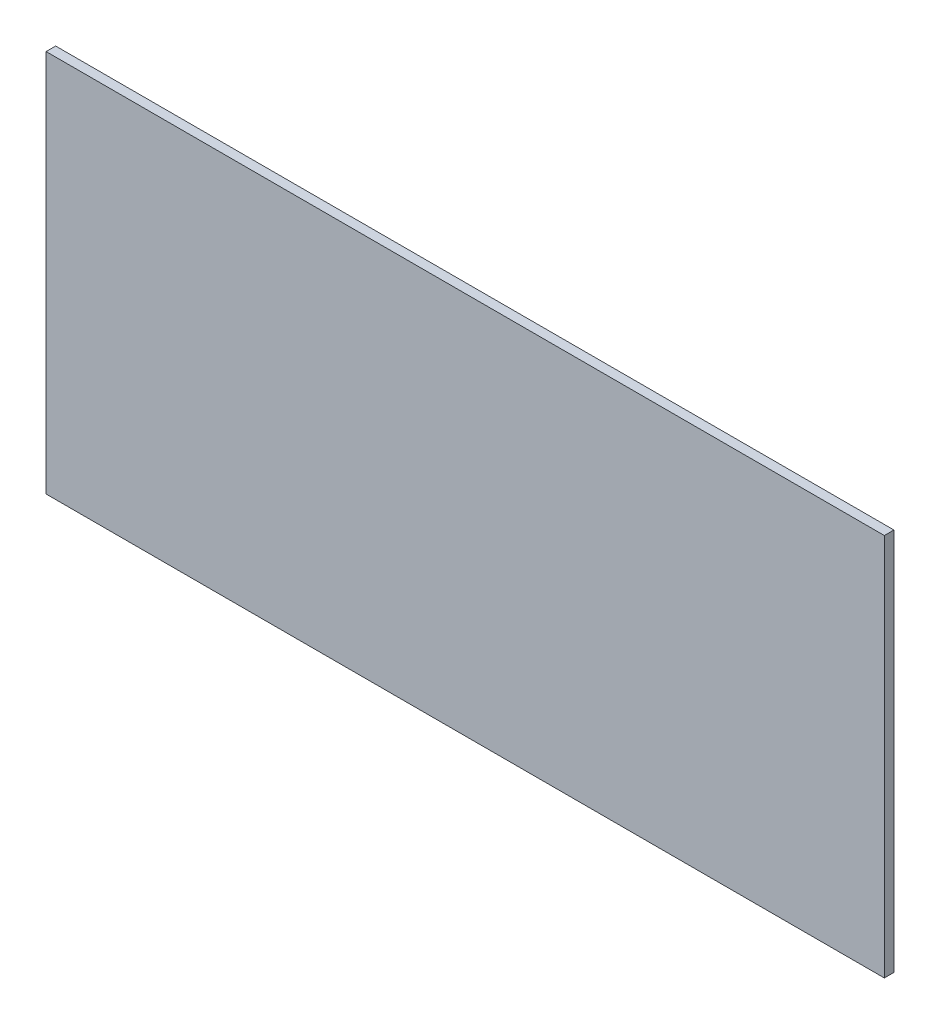
SolidWorks part; units mm, degrees
ref_plane "前视基准面" through (0, 0, 0) normal (0, 0, 1) x (1, 0, 0)
ref_plane "上视基准面" through (0, 0, 0) normal (0, 1, 0) x (1, 0, 0)
ref_plane "右视基准面" through (0, 0, 0) normal (1, 0, 0) x (0, 0, -1)
sketch "草图1" plane through (0, 0, 0) normal (0, 0, 1) x (1, 0, 0)
  line L1 (-175, -80) -> (175, -80)
  line L2 (-175, -80) -> (-175, 80)
  line L3 (-175, 80) -> (175, 80)
  line L4 (175, -80) -> (175, 80)
  line L5 (-175, -80) -> (175, 80) construction
  line L6 (-175, 80) -> (175, -80) construction
  point P0 (0, 0)
  dimension "D1" = 350
  dimension "D2" = 160
extrude "凸台-拉伸1" add sketch "草图1" along normal blind 4
